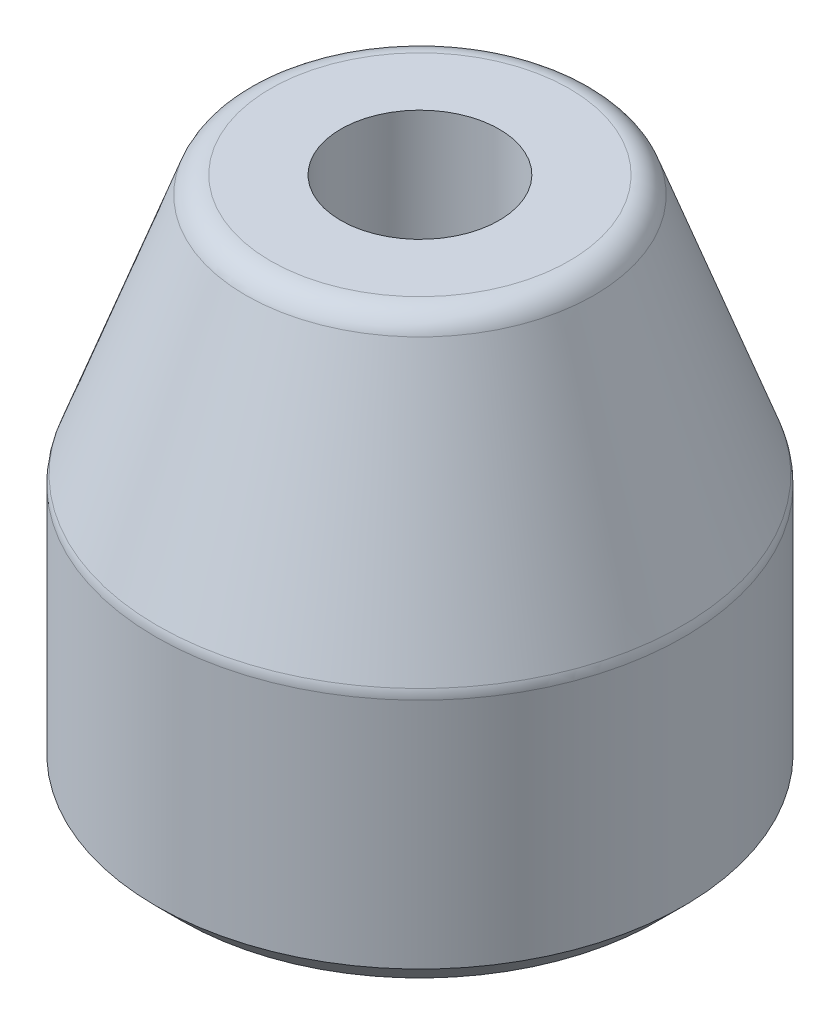
SolidWorks part; units mm, degrees
ref_plane "Front Plane" through (0, 0, 0) normal (0, 0, 1) x (1, 0, 0)
ref_plane "Top Plane" through (0, 0, 0) normal (0, 1, 0) x (1, 0, 0)
ref_plane "Right Plane" through (0, 0, 0) normal (1, 0, 0) x (0, 0, -1)
sketch "Sketch1" plane through (0, 0, 0) normal (0, 1, 0) x (1, 0, 0)
  circle A1 centre (0, 0) radius 5
  dimension "D1" = 10
extrude "Boss-Extrude1" add sketch "Sketch1" along normal blind 10 contours A1
sketch "Sketch2" plane through (0, 10, 0) normal (0, 1, 0) x (1, 0, 0)
  circle A0 centre (0, 0) radius 1.5
  dimension "D1" = 3
extrude "Cut-Extrude1" cut sketch "Sketch2" against normal through all
chamfer "Chamfer1" distance 5 angle 20 1 edges at (0, 10, 5)
sketch "Sketch3" plane through (0, 0, 0) normal (0, -1, 0) x (1, 0, 0)
  circle A0 centre (0, 0) radius 3.25
  dimension "D1" = 6.5
extrude "Cut-Extrude2" cut sketch "Sketch3" against normal blind 6.9409 draft 0.5
chamfer "Chamfer2" distance 0.5 angle 45 2 edges at (0, 0, 5) (0, 0, -3.25)
fillet "Fillet1" radius 0.5 2 edges at (0, 5, 5) (0, 10, 3.1801)
